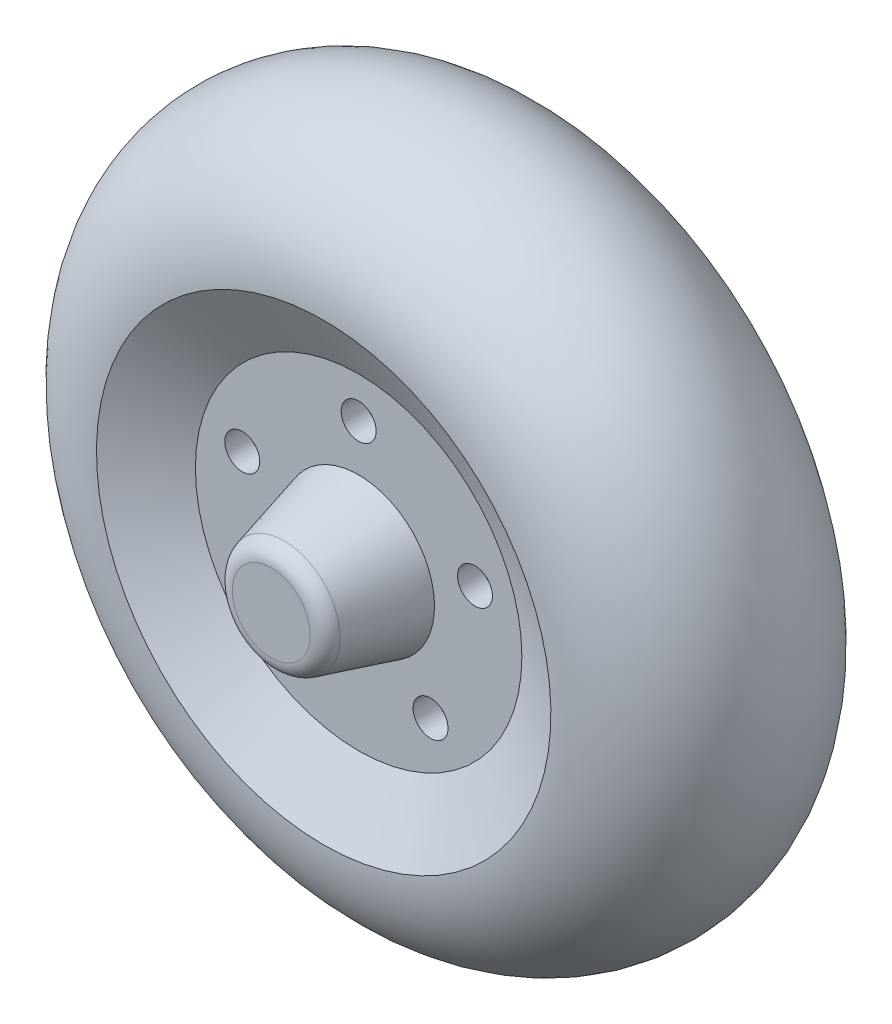
SolidWorks part; units mm, degrees
material "Laiton"
ref_plane "Plan de face" through (0, 0, 0) normal (0, 0, 1) x (1, 0, 0)
ref_plane "Plan de dessus" through (0, 0, 0) normal (0, 1, 0) x (1, 0, 0)
ref_plane "Plan de droite" through (0, 0, 0) normal (1, 0, 0) x (0, 0, -1)
sketch "Esquisse1" plane through (0, 0, 0) normal (1, 0, 0) x (0, 0, -1)
  line L0 (0, 100) -> (0, -100) construction
  line L1 (-50, 15) -> (-50, 0)
  line L2 (-50, 15) -> (-25, 21.6987)
  line L3 (-25, 46.6987) -> (-25, 21.6987)
  line L4 (-35, 65) -> (-25, 46.6987)
  line L5 (35, 65) -> (25, 46.6987)
  line L6 (25, 46.6987) -> (25, 21.6987)
  line L7 (50, 15) -> (25, 21.6987)
  line L8 (50, 15) -> (50, 0)
  line L9 (43, 9.6287) -> (43, 0)
  line L10 (43, 9.6287) -> (18, 16.3274)
  line L11 (18, 48.4864) -> (18, 16.3274)
  line L12 (27.9487, 66.6939) -> (18, 48.4864)
  line L13 (-27.9487, 66.6939) -> (-18, 48.4864)
  line L14 (-18, 48.4864) -> (-18, 16.3274)
  line L15 (-43, 9.6287) -> (-18, 16.3274)
  line L16 (-43, 9.6287) -> (-43, 0)
  line L17 (-50, 0) -> (-43, 0)
  line L18 (43, 0) -> (50, 0)
  line L19 (0, 0) -> (32.065, 0) construction
  arc A0 (35, 65) -> (-35, 65) centre (0, 65) ccw
  arc A1 (27.9487, 66.6939) -> (-27.9487, 66.6939) centre (0, 65) ccw
  point P2 (0, 0)
  dimension "D7" = 35
  dimension "D2" = 15
  dimension "D3" = 50
  dimension "D4" = 105
  dimension "D5" = 25
  dimension "D6" = 25
  dimension "D1" = 200
  dimension "D8" = 7
revolve "Révolution1" add sketch "Esquisse1" angle 360 about L19
fillet "Congé1" radius 5 2 edges at (0, -15, 50) (0, -15, -50)
sketch "Esquisse2" plane through (0, 0, -50) normal (0, 0, -1) x (-1, 0, 0)
  circle A0 centre (0, 0) radius 35 construction
  circle A1 centre (0, 35) radius 5
  circle A2 centre (33.287, 10.8156) radius 5
  circle A3 centre (20.5725, -28.3156) radius 5
  circle A4 centre (-20.5725, -28.3156) radius 5
  circle A5 centre (-33.287, 10.8156) radius 5
  point P16 (0, 0)
  dimension "D1" = 70
  dimension "D2" = 10
extrude "Enlèv. mat.-Extru.1" cut sketch "Esquisse2" against normal through all
equation "\"A\"= 50"
equation "\"B\"= 30"
equation "\"C\"= 35"
equation "\"D\"= \"A\" * 4"
equation "\"D2@Esquisse1\"=\"B\" / 2"
equation "\"D3@Esquisse1\"=\"A\""
equation "\"D6@Esquisse1\"=\"A\" / 2"
equation "\"D1@Esquisse1\"=\"D\""
equation "\"D7@Esquisse1\"=\"C\""
equation "\"D1@Esquisse2\"=\"C\" * 2"
